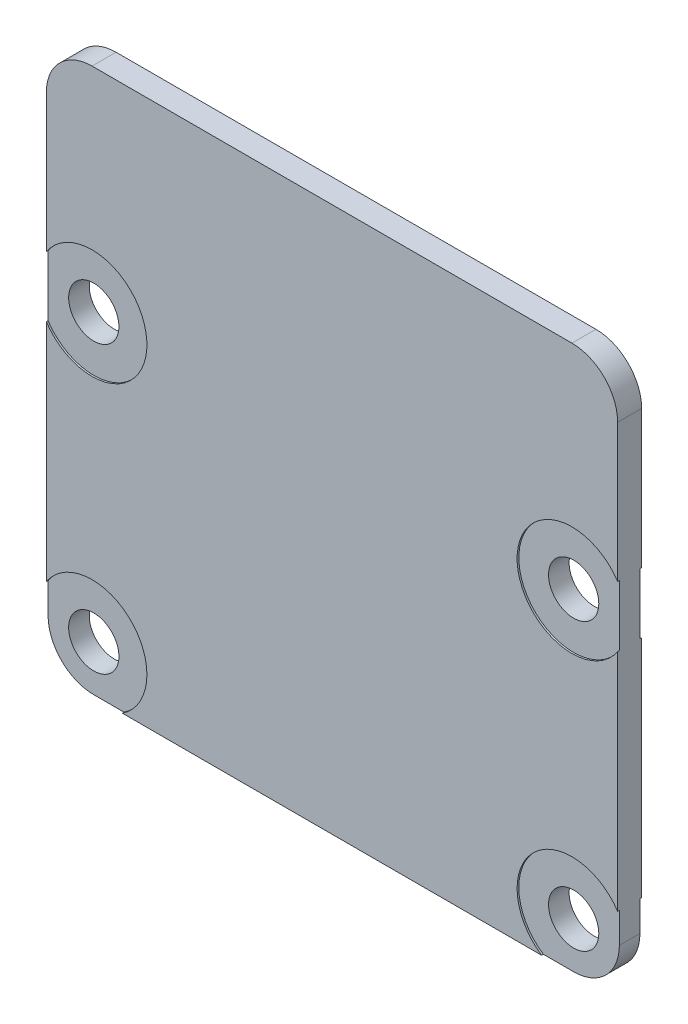
SolidWorks part; units mm, degrees
ref_plane "Front Plane" through (0, 0, 0) normal (0, 0, 1) x (1, 0, 0)
ref_plane "Top Plane" through (0, 0, 0) normal (0, 1, 0) x (1, 0, 0)
ref_plane "Right Plane" through (0, 0, 0) normal (1, 0, 0) x (0, 0, -1)
sketch "Sketch2" plane through (0, 0, 0) normal (0, 0, 1) x (1, 0, 0)
  line L1 (-4.25, 4.25) -> (4.25, 4.25) construction
  line L2 (-4.25, 4.25) -> (-4.25, -4.25) construction
  line L3 (-4.25, -4.25) -> (4.25, -4.25) construction
  line L4 (4.25, 4.25) -> (4.25, -4.25) construction
  line L5 (-4.25, 4.25) -> (4.25, -4.25) construction
  line L6 (-4.25, -4.25) -> (4.25, 4.25) construction
  line L7 (-12.5, 9.462) -> (12.5, 9.462) construction
  line L8 (-12.5, 9.462) -> (-12.5, -14.4) construction
  line L9 (-12.5, -14.4) -> (12.5, -14.4) construction
  line L10 (12.5, 9.462) -> (12.5, -14.4) construction
  line L11 (-2.81, -11.19) -> (5.41, -11.19) construction
  line L12 (-2.81, -11.19) -> (-2.81, -8.21) construction
  line L13 (-2.81, -8.21) -> (5.41, -8.21) construction
  line L14 (5.41, -11.19) -> (5.41, -8.21) construction
  line L15 (-2.81, -11.19) -> (5.41, -8.21) construction
  line L16 (-2.81, -8.21) -> (5.41, -11.19) construction
  line L17 (-10.5, 0.1) -> (10.5, 0.1) construction
  line L18 (-10.5, 0.1) -> (-10.5, -12.4) construction
  line L19 (-10.5, -12.4) -> (10.5, -12.4) construction
  line L20 (10.5, 0.1) -> (10.5, -12.4) construction
  circle A0 centre (-10.5, 0.1) radius 1.1 construction
  circle A1 centre (10.5, 0.1) radius 1.1 construction
  circle A2 centre (10.5, -12.4) radius 1.1 construction
  circle A3 centre (-10.5, -12.4) radius 1.1 construction
  point P0 (0, 0)
  point P10 (1.3, -9.7)
  point P23 (0, 0)
  dimension "D14" = 2.2
  dimension "D1" = 8.5
  dimension "D2" = 23.862
  dimension "D3" = 25
  dimension "D4" = 12.5
  dimension "D5" = 9.462
  dimension "D6" = 4.7
  dimension "D7" = 13.8
  dimension "D8" = 8.22
  dimension "D9" = 2.98
  dimension "D10" = 2
  dimension "D11" = 2
  dimension "D12" = 2
  dimension "D13" = 14.5
sketch "Sketch3" plane through (0, 0, 0) normal (0, 0, 1) x (1, 0, 0)
  line L0 (-12.5, -14.4) -> (12.5, -14.4) construction
  line L1 (-12.5, 9.462) -> (-12.5, -14.4) construction
  line L2 (12.5, 9.462) -> (12.5, -14.4) construction
  line L3 (-12.5, 9.462) -> (12.5, 9.462) construction
  line L4 (-12.5, -14.4) -> (12.5, -14.4)
  line L5 (-12.5, 9.462) -> (-12.5, -14.4)
  line L6 (12.5, 9.462) -> (12.5, -14.4)
  line L7 (-12.5, 9.462) -> (12.5, 9.462)
extrude "Boss-Extrude1" add sketch "Sketch3" against normal blind 0.9
fillet "Fillet1" radius 2 4 edges at (-12.5, -14.4, -0.45) (12.5, -14.4, -0.45) (-12.5, 9.462, -0.45) (12.5, 9.462, -0.45)
sketch "Sketch4" plane through (0, 0, 0) normal (0, 0, 1) x (1, 0, 0)
  circle A0 centre (-10.5, 0.1) radius 1.1 construction
  circle A1 centre (-10.5, -12.4) radius 1.1 construction
  circle A2 centre (10.5, -12.4) radius 1.1 construction
  circle A3 centre (10.5, 0.1) radius 1.1 construction
  circle A4 centre (-10.5, 0.1) radius 1.1
  circle A5 centre (-10.5, -12.4) radius 1.1
  circle A6 centre (10.5, -12.4) radius 1.1
  circle A7 centre (10.5, 0.1) radius 1.1
extrude "Cut-Extrude1" cut sketch "Sketch4" against normal through all
sketch "Sketch5" plane through (0, 0, 0) normal (0, 0, 1) x (1, 0, 0)
  line L0 (12.5, 1.4266) -> (12.5, 7.462)
  line L1 (-12.5, -1.2266) -> (-12.5, -11.0734)
  line L4 (-12.5, 7.462) -> (-12.5, -12.4)
  line L5 (-10.5, -14.4) -> (10.5, -14.4)
  line L6 (12.5, -12.4) -> (12.5, 7.462)
  line L7 (10.5, 9.462) -> (-10.5, 9.462)
  line L8 (-12.5, 7.462) -> (-12.5, 1.4266)
  line L9 (-9.1734, -14.4) -> (9.1734, -14.4)
  line L10 (12.5, -11.0734) -> (12.5, -1.2266)
  line L11 (10.5, 9.462) -> (-10.5, 9.462)
  arc A0 (12.5, 1.4266) -> (12.5, -1.2266) centre (10.5, 0.1) ccw
  arc A1 (-12.5, -1.2266) -> (-12.5, 1.4266) centre (-10.5, 0.1) ccw
  arc A2 (-9.1734, -14.4) -> (-12.5, -11.0734) centre (-10.5, -12.4) ccw
  arc A3 (12.5, -11.0734) -> (9.1734, -14.4) centre (10.5, -12.4) ccw
  arc A4 (-12.5, -12.4) -> (-10.5, -14.4) centre (-10.5, -12.4) ccw
  arc A5 (10.5, -14.4) -> (12.5, -12.4) centre (10.5, -12.4) ccw
  arc A6 (12.5, 7.462) -> (10.5, 9.462) centre (10.5, 7.462) ccw
  arc A7 (-10.5, 9.462) -> (-12.5, 7.462) centre (-10.5, 7.462) ccw
  arc A10 (12.5, 7.462) -> (10.5, 9.462) centre (10.5, 7.462) ccw
  arc A11 (-10.5, 9.462) -> (-12.5, 7.462) centre (-10.5, 7.462) ccw
  dimension "D2" = 4.8
  dimension "D1" = 0
extrude "Boss-Extrude2" add sketch "Sketch5" along normal blind 0.075
sketch "Sketch6" plane through (0, 0, -0.9) normal (0, 0, -1) x (-1, 0, 0)
  line L6 (12.5, 1.4266) -> (12.5, 7.462)
  line L7 (12.5, -11.0734) -> (12.5, -1.2266)
  line L8 (-9.1734, -14.4) -> (9.1734, -14.4)
  line L9 (-12.5, -1.2266) -> (-12.5, -11.0734)
  line L10 (-12.5, 7.462) -> (-12.5, 1.4266)
  line L11 (10.5, 9.462) -> (-10.5, 9.462)
  line L12 (12.5, 1.4266) -> (12.5, 7.462)
  line L13 (12.5, -11.0734) -> (12.5, -1.2266)
  line L14 (-9.1734, -14.4) -> (9.1734, -14.4)
  line L15 (-12.5, -1.2266) -> (-12.5, -11.0734)
  line L16 (-12.5, 7.462) -> (-12.5, 1.4266)
  line L17 (10.5, 9.462) -> (-10.5, 9.462)
  arc A6 (12.5, 7.462) -> (10.5, 9.462) centre (10.5, 7.462) ccw
  arc A7 (12.5, 1.4266) -> (12.5, -1.2266) centre (10.5, 0.1) ccw
  arc A8 (12.5, -11.0734) -> (9.1734, -14.4) centre (10.5, -12.4) ccw
  arc A9 (-9.1734, -14.4) -> (-12.5, -11.0734) centre (-10.5, -12.4) ccw
  arc A10 (-12.5, -1.2266) -> (-12.5, 1.4266) centre (-10.5, 0.1) ccw
  arc A11 (-10.5, 9.462) -> (-12.5, 7.462) centre (-10.5, 7.462) ccw
  arc A12 (12.5, 7.462) -> (10.5, 9.462) centre (10.5, 7.462) ccw
  arc A13 (12.5, 1.4266) -> (12.5, -1.2266) centre (10.5, 0.1) ccw
  arc A14 (12.5, -11.0734) -> (9.1734, -14.4) centre (10.5, -12.4) ccw
  arc A15 (-9.1734, -14.4) -> (-12.5, -11.0734) centre (-10.5, -12.4) ccw
  arc A16 (-12.5, -1.2266) -> (-12.5, 1.4266) centre (-10.5, 0.1) ccw
  arc A17 (-10.5, 9.462) -> (-12.5, 7.462) centre (-10.5, 7.462) ccw
  dimension "D1" = 0
extrude "Boss-Extrude3" add sketch "Sketch6" along normal blind 0.075
sketch "Sketch7" plane through (0, 0, 0.075) normal (0, 0, 1) x (1, 0, 0)
  line L0 (-2.81, -11.19) -> (-2.81, -8.21) construction
  line L1 (5.41, -11.19) -> (5.41, -8.21) construction
  line L2 (-2.81, -8.21) -> (5.41, -11.19) construction
  line L3 (-2.81, -11.19) -> (5.41, -8.21) construction
  line L4 (-2.81, -8.21) -> (5.41, -8.21) construction
  line L5 (-2.81, -11.19) -> (5.41, -11.19) construction
  line L6 (-2.81, -11.19) -> (-2.81, -8.21) construction
  line L7 (5.41, -11.19) -> (5.41, -8.21) construction
  line L8 (-2.81, -8.21) -> (5.41, -11.19) construction
  line L9 (-2.81, -11.19) -> (5.41, -8.21) construction
  line L10 (-2.81, -8.21) -> (5.41, -8.21) construction
  line L11 (-2.81, -11.19) -> (5.41, -11.19) construction
  point P0 (1.3, -9.7)
  point P6 (0, 0)
sketch "Sketch9" plane through (0, 0, 0) normal (0, 1, 0) x (1, 0, 0)
  line L0 (0, 0) -> (0, -17.1807) construction
